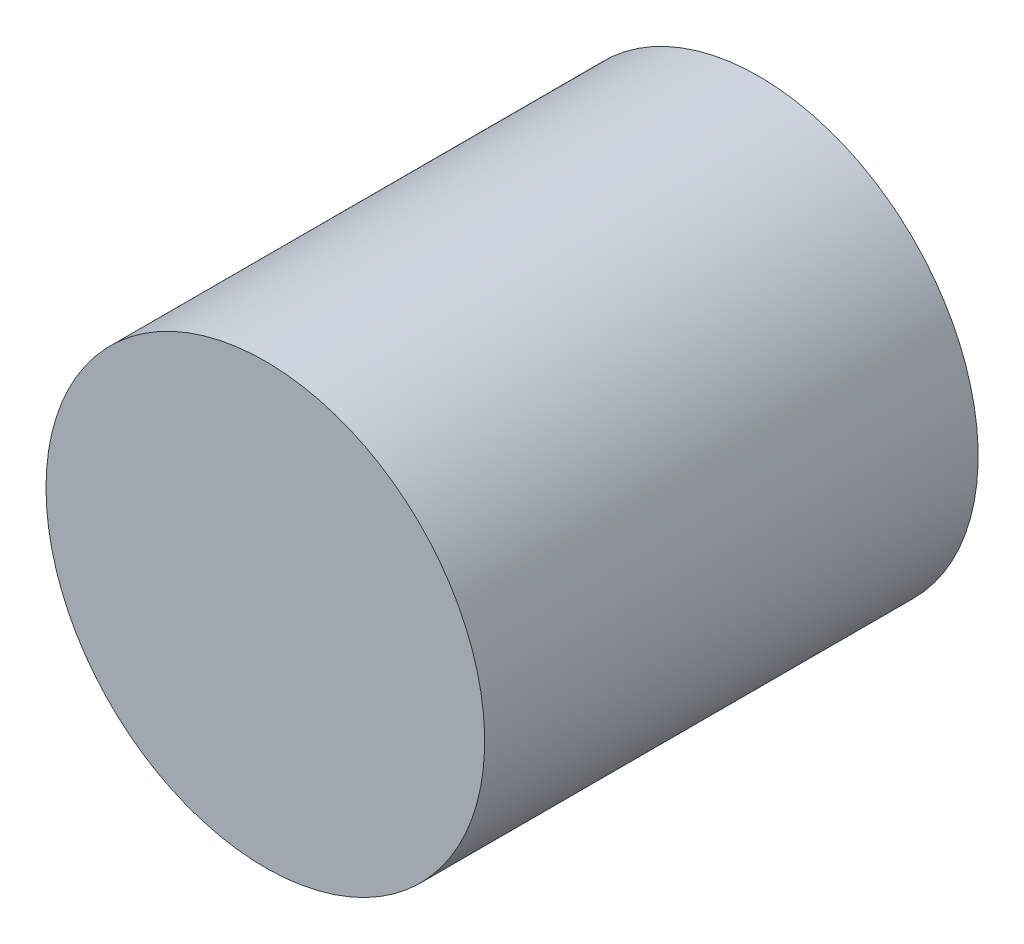
SolidWorks part; units mm, degrees
ref_plane "Front Plane" through (0, 0, 0) normal (0, 0, 1) x (1, 0, 0)
ref_plane "Top Plane" through (0, 0, 0) normal (0, 1, 0) x (1, 0, 0)
ref_plane "Right Plane" through (0, 0, 0) normal (1, 0, 0) x (0, 0, -1)
sketch "Sketch1" plane through (0, 0, 0) normal (0, 0, 1) x (1, 0, 0)
  circle A0 centre (0, 0) radius 20
  dimension "D1" = 40
extrude "Boss-Extrude1" add sketch "Sketch1" along normal blind 45
